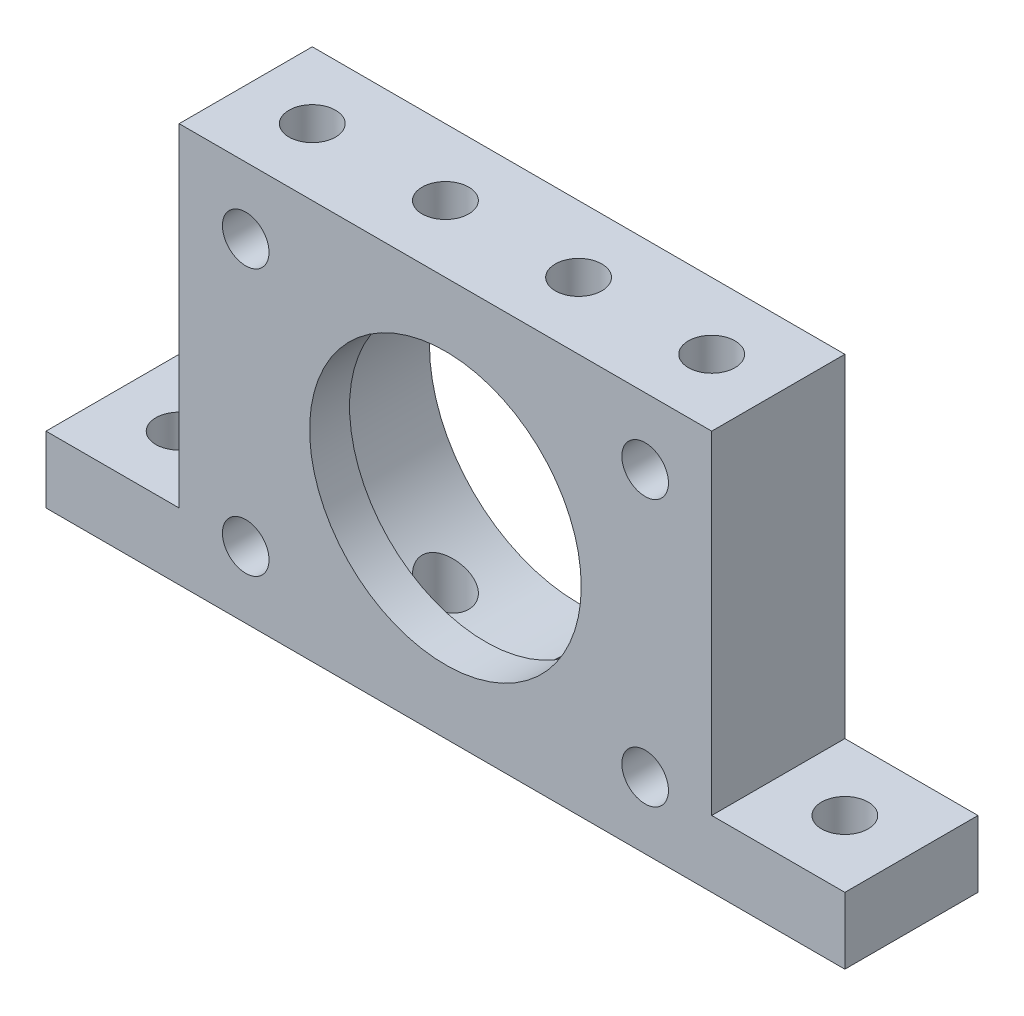
SolidWorks part; units mm, degrees
ref_plane "Plan de face" through (0, 0, 0) normal (0, 0, 1) x (1, 0, 0)
ref_plane "Plan de dessus" through (0, 0, 0) normal (0, 1, 0) x (1, 0, 0)
ref_plane "Plan de droite" through (0, 0, 0) normal (1, 0, 0) x (0, 0, -1)
sketch "Esquisse1" plane through (0, 0, 0) normal (0, 0, 1) x (1, 0, 0)
  line L0 (-20, -10) -> (-20, 15)
  line L1 (-20, 15) -> (20, 15)
  line L2 (20, 15) -> (20, -10)
  line L3 (20, -10) -> (-20, -10) construction
  line L4 (0, 26.751) -> (0, -33.9532) construction
  line L5 (-20, -10) -> (-30, -10)
  line L6 (-30, -10) -> (-30, -15)
  line L7 (-30, -15) -> (30, -15)
  line L8 (30, -15) -> (30, -10)
  line L9 (30, -10) -> (20, -10)
  circle A0 centre (0, 0) radius 11.2
  circle A1 centre (15, 10) radius 1.75
  circle A2 centre (-15, 10) radius 1.75
  circle A3 centre (-15, -10) radius 1.75
  circle A4 centre (15, -10) radius 1.75
  dimension "D1" = 22.4
  dimension "D10" = 3.5
  dimension "D2" = 15
  dimension "D3" = 10
  dimension "D4" = 40
  dimension "D5" = 10
  dimension "D6" = 25
  dimension "D7" = 5
  dimension "D8" = 5
  dimension "D9" = 5
  dimension "D11" = 2
  dimension "D12" = 2
extrude "Boss.-Extru.1" add sketch "Esquisse1" along normal blind 10
sketch "Esquisse2" plane through (0, 0, 10) normal (0, 0, 1) x (1, 0, 0)
  circle A0 centre (0, 0) radius 11.2
  circle A1 centre (0, 0) radius 10.2
  circle A2 centre (0, 0) radius 11.2 construction
  dimension "D1" = 1
extrude "Boss.-Extru.2" add sketch "Esquisse2" against normal offset from surface (3 mm away) 7 up to face at (0, -5, 0)
sketch "Esquisse3" plane through (0, -15, 0) normal (0, -1, 0) x (1, 0, 0)
  line L0 (-30, 5) -> (30, 5) construction
  line L1 (-30, 10) -> (-30, 0) construction
  line L2 (30, 10) -> (30, 0) construction
  circle A0 centre (-25, 5) radius 1.75
  circle A1 centre (-15, 5) radius 1.75
  circle A2 centre (-5, 5) radius 1.75
  circle A3 centre (5, 5) radius 1.75
  circle A4 centre (15, 5) radius 1.75
  circle A5 centre (25, 5) radius 1.75
  dimension "D2" = 3.5
  dimension "D1" = 5
  dimension "D3" = 6
extrude "Enlèv. mat.-Extru.1" cut sketch "Esquisse3" against normal through all
